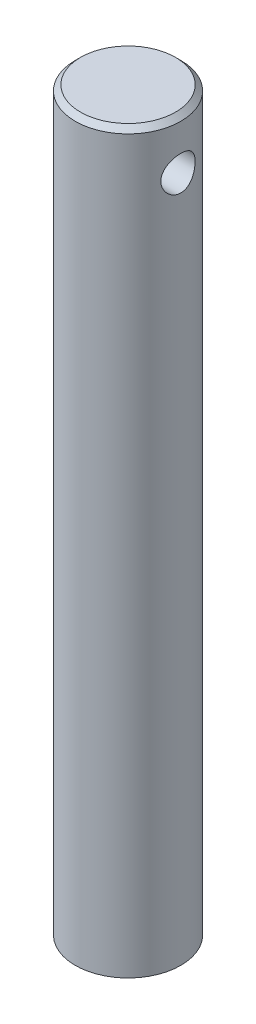
SolidWorks part; units mm, degrees
ref_plane "前视基准面" through (0, 0, 0) normal (0, 0, 1) x (1, 0, 0)
ref_plane "上视基准面" through (0, 0, 0) normal (0, 1, 0) x (1, 0, 0)
ref_plane "右视基准面" through (0, 0, 0) normal (1, 0, 0) x (0, 0, -1)
sketch "草图1" plane through (0, 0, 0) normal (0, 0, 1) x (1, 0, 0)
  line L0 (10, 9.5) -> (0, 9.5)
  line L1 (0, 9.5) -> (0, -130)
  line L2 (0, -130) -> (10, -130)
  line L3 (10, -130) -> (10, 9.5)
  line L4 (0, 9.5) -> (0, -130) construction
revolve "旋转1" add sketch "草图1" angle 360 about L4
hole_wizard "Ø6.5 (6.5) 直径孔1" positions "3D草图1" profile "草图2" hole size "Ø6.5" standard "ANSI Metric"
sketch3d "3D草图1"
  point P0 (-10, 0, 0)
sketch "草图2" plane through (-10, 0, 0) normal (0, 1, 0) x (0, 0, 1)
  line L0 (0, 0) -> (0, 20)
  line L1 (0, 20) -> (3.25, 20)
  line L2 (3.25, 20) -> (3.25, 0)
  line L5 (3.25, 0) -> (0, 0)
  line L11 (0, -6.35) -> (0, 107.95) construction
  dimension "通孔孔直径" = 6.5
  dimension "通孔孔深度" = 20
chamfer "倒角1" distance 1 angle 45 1 edges at (10, 9.5, 0)
